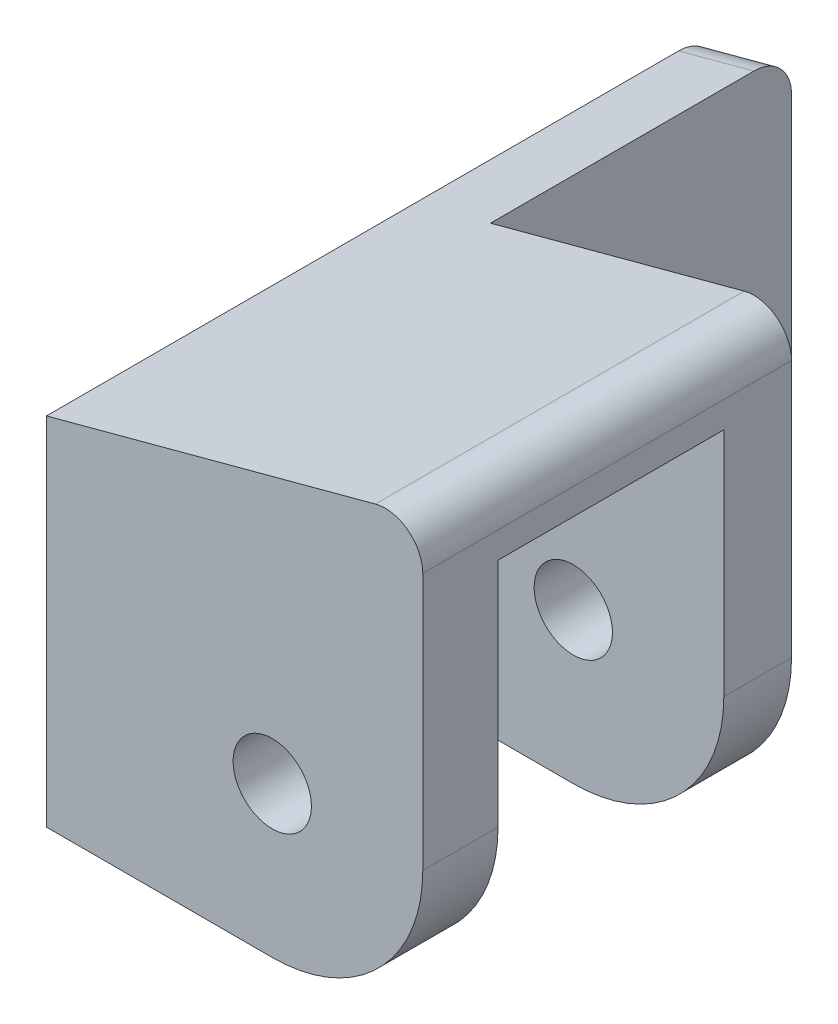
SolidWorks part; units mm, degrees
ref_plane "Спереди" through (0, 0, 0) normal (0, 0, 1) x (1, 0, 0)
ref_plane "Сверху" through (0, 0, 0) normal (0, 1, 0) x (1, 0, 0)
ref_plane "Справа" through (0, 0, 0) normal (1, 0, 0) x (0, 0, -1)
sketch "Эскиз1" plane through (0, 0, 0) normal (0, 0, 1) x (1, 0, 0)
  line L0 (10, 0) -> (-10, 0) construction
  line L1 (10, 10) -> (-10, 10)
  line L2 (10, 10) -> (10, -15.359)
  line L3 (10, -15.359) -> (-10, -10)
  line L4 (-10, 10) -> (-10, -10)
  circle A2 centre (0, 0) radius 10 construction
  point P11 (0, 0)
  dimension "D1" = 20
  dimension "D2" = 105
  dimension "D3" = 20
extrude "Бобышка-Вытянуть1" add sketch "Эскиз1" along normal blind 4.5
sketch "Эскиз10" plane through (0, 0, 0) normal (0, 0, -1) x (-1, 0, 0)
  line L1 (15, 10) -> (15, -13.6603)
  line L2 (15, -13.6603) -> (-10, -20.359)
  line L3 (-10, -20.359) -> (-10, -15.359)
  line L4 (10, -10) -> (-10, -15.359)
  line L5 (10, -10) -> (10, 10)
  line L6 (10, -10) -> (-10, -15.359) construction
  line L13 (10, 10) -> (15, 10)
  dimension "D1" = 5
  dimension "D6" = 5
extrude "Бобышка-Вытянуть5" add sketch "Эскиз10" against normal offset from surface (19.5 mm away) 15 up to face at (0, -1.3397, 4.5) offset beyond the face yes
sketch "Эскиз11" plane through (0, 0, 0) normal (0, 0, -1) x (-1, 0, 0)
  line L0 (-10, -20.359) -> (15, -13.6603) construction
  line L1 (15, 10) -> (10, 10)
  line L2 (15, 10) -> (15, -13.6603)
  line L3 (15, -13.6603) -> (10, -15)
  line L4 (10, 10) -> (10, -15)
  line L6 (-10, 10) -> (15, 10) construction
  dimension "D1" = 5
extrude "Бобышка-Вытянуть6" add sketch "Эскиз11" along normal blind 20
sketch "Эскиз12" plane through (0, 0, 19.5) normal (0, 0, 1) x (1, 0, 0)
  line L0 (-15, -13.6603) -> (10, -20.359) construction
  line L1 (-15, -13.6603) -> (10, -20.359)
  line L2 (-15, -13.6603) -> (-15, 10)
  line L3 (-15, 10) -> (10, 10)
  line L4 (10, -20.359) -> (10, 10)
  line L5 (10, -20.359) -> (10, -15.359) construction
extrude "Бобышка-Вытянуть7" add sketch "Эскиз12" along normal blind 5
sketch "Эскиз6" plane through (0, 0, 0) normal (0, 0, -1) x (-1, 0, 0)
  circle A0 centre (0, 0) radius 2.6
  dimension "D1" = 5.2
extrude "Вырез-Вытянуть1" cut sketch "Эскиз6" against normal through all
sketch "Эскиз13" plane through (-15, 0, 0) normal (-1, 0, 0) x (0, 0, 1)
  line L0 (-20, -13.6603) -> (-20, 10) construction
  circle A0 centre (-10, -1.8301) radius 2.6
  point P4 (-20, -1.8301)
  dimension "D1" = 5.2
  dimension "D2" = 10
extrude "Вырез-Вытянуть2" cut sketch "Эскиз13" against normal through all
fillet "Скругление1" radius 2.5 3 edges at (-12.5, -14.3301, -20) (-12.5, 10, -20) (10, -20.359, 12.25)
fillet "Скругление2" radius 10 2 edges at (10, 10, 2.25) (10, 10, 22)
mirror "Зеркальное отражение1" about plane through (0, 0, 0) normal (0, 1, 0) of bodies 112
delete or keep bodies "Тело-Удалить/Сохранить 1" type delete bodies bodies 112
